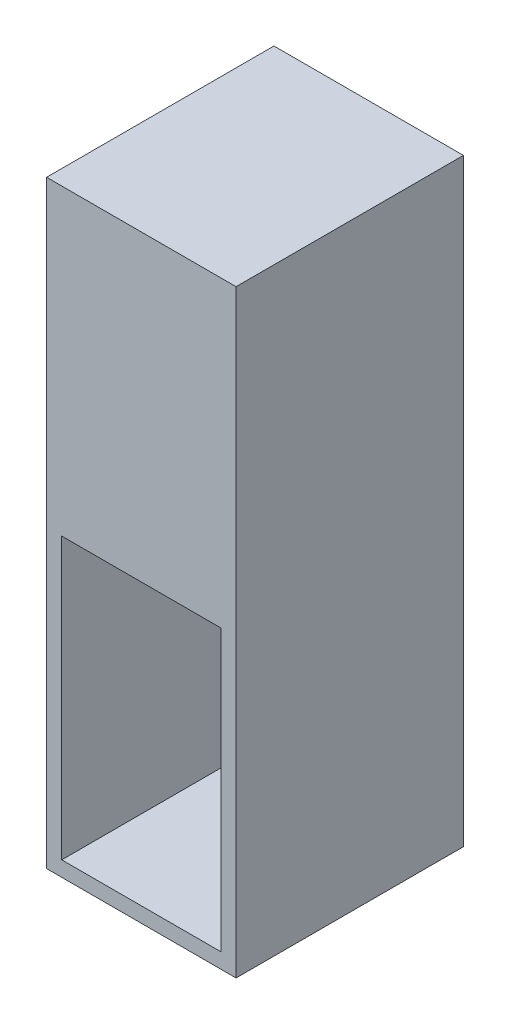
SolidWorks part; units mm, degrees
ref_plane "Front Plane" through (0, 0, 0) normal (0, 0, 1) x (1, 0, 0)
ref_plane "Top Plane" through (0, 0, 0) normal (0, 1, 0) x (1, 0, 0)
ref_plane "Right Plane" through (0, 0, 0) normal (1, 0, 0) x (0, 0, -1)
sketch "Sketch1" plane through (0, 0, 0) normal (0, 0, 1) x (1, 0, 0)
  line L1 (-89.3763, 55.4682) -> (-64.3763, 55.4682)
  line L2 (-89.3763, 55.4682) -> (-89.3763, -23.5318)
  line L3 (-89.3763, -23.5318) -> (-64.3763, -23.5318)
  line L4 (-64.3763, 55.4682) -> (-64.3763, -23.5318)
  dimension "D1" = 25
  dimension "D2" = 79
extrude "Boss-Extrude1" add sketch "Sketch1" along normal blind 30
sketch "Sketch2" plane through (0, 0, 30) normal (0, 0, 1) x (1, 0, 0)
  line L0 (-89.3763, 55.4682) -> (-89.3763, -23.5318) construction
  line L1 (-87.3763, -21.5318) -> (-66.3763, -21.5318)
  line L2 (-87.3763, -21.5318) -> (-87.3763, 15.4682)
  line L3 (-87.3763, 15.4682) -> (-66.3763, 15.4682)
  line L4 (-66.3763, -21.5318) -> (-66.3763, 15.4682)
  line L5 (-89.3763, -23.5318) -> (-64.3763, -23.5318) construction
  dimension "D1" = 21
  dimension "D2" = 2
  dimension "D3" = 2
  dimension "D4" = 37
extrude "Cut-Extrude1" cut sketch "Sketch2" against normal blind 30
sketch "Sketch3" plane through (0, 55.4682, 0) normal (0, 1, 0) x (1, 0, 0)
  line L0 (-64.3763, -30) -> (-89.3763, -30) construction
  line L1 (-68.3359, -30) -> (-86.3868, -30)
  line L2 (-68.3359, -30) -> (-68.3359, 0)
  line L3 (-68.3359, 0) -> (-86.3868, 0)
  line L4 (-86.3868, -30) -> (-86.3868, 0)
  line L5 (-64.3763, 0) -> (-89.3763, 0) construction
  line L6 (-64.3763, -30) -> (-64.3763, 0) construction
  dimension "D1" = 3.9596
